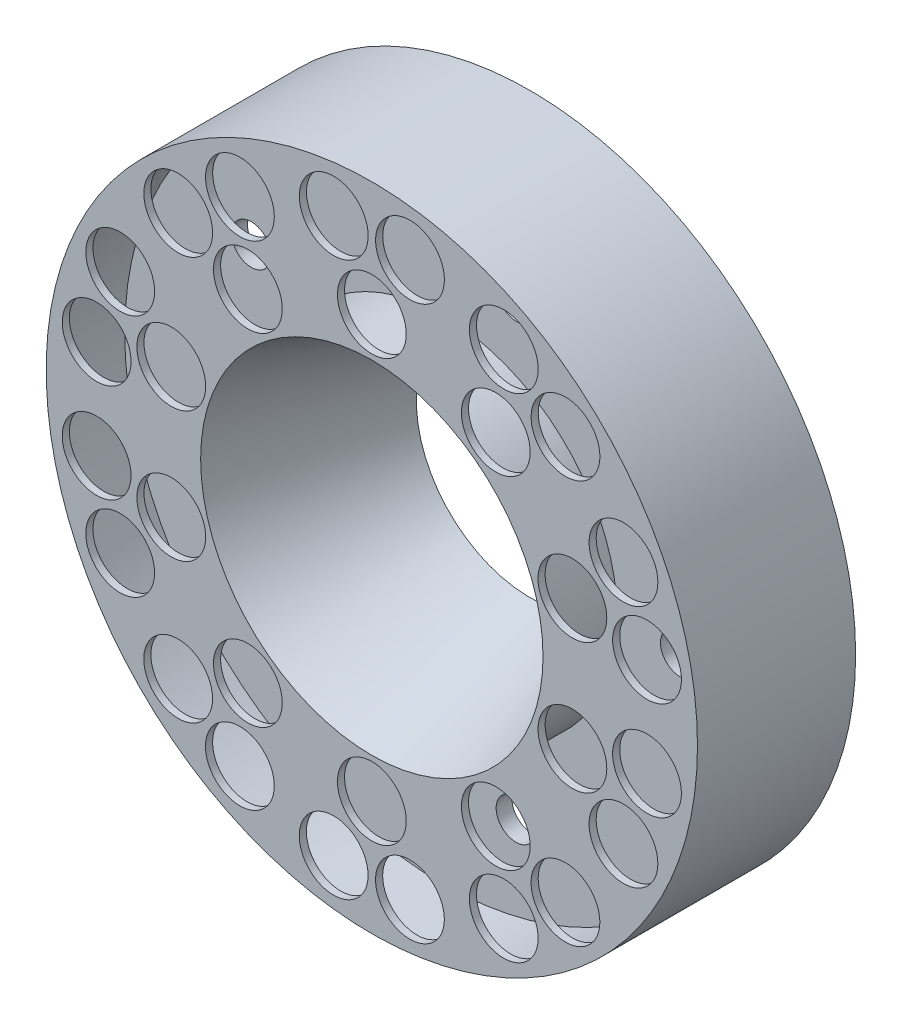
SolidWorks part; units mm, degrees
ref_plane "Front Plane" through (0, 0, 0) normal (0, 0, 1) x (1, 0, 0)
ref_plane "Top Plane" through (0, 0, 0) normal (0, 1, 0) x (1, 0, 0)
ref_plane "Right Plane" through (0, 0, 0) normal (1, 0, 0) x (0, 0, -1)
sketch "Sketch1" plane through (0, 0, 0) normal (0, 0, 1) x (1, 0, 0)
  circle A7 centre (-38.9246, 36.7467) radius 104.6074
extrude "Boss-Extrude6" add sketch "Sketch1" along normal blind 50.8
sketch "Sketch4" plane through (0, 0, 50.8) normal (0, 0, 1) x (1, 0, 0)
  circle A5 centre (-38.9246, 36.7467) radius 54.991
  dimension "D1" = 109.982
extrude "Cut-Extrude2" cut sketch "Sketch4" against normal blind 109.982 draft 20 contours A5
sketch "Sketch6" plane through (0, 0, 50.8) normal (0, 0, 1) x (1, 0, 0)
  circle A9 centre (23.2878, 101.5139) radius 11.049
  circle A10 centre (-26.663, 125.712) radius 11.049
  circle A11 centre (-38.9246, 104.4853) radius 11.049
  circle A12 centre (-51.1655, 125.712) radius 11.049
  circle A13 centre (0.8912, 91.5484) radius 11.049
  circle A14 centre (3.4648, 115.9162) radius 11.049
  circle A15 centre (49.4755, 52.577) radius 11.049
  circle A16 centre (25.4987, 57.6791) radius 11.049
  circle A17 centre (41.9038, 75.8803) radius 11.049
  circle A18 centre (41.8974, -2.4066) radius 11.049
  circle A19 centre (25.4987, 15.8143) radius 11.049
  circle A20 centre (49.4691, 20.8967) radius 11.049
  circle A21 centre (3.4481, -42.435) radius 11.049
  circle A22 centre (0.8912, -18.055) radius 11.049
  circle A23 centre (23.271, -28.0327) radius 11.049
  circle A24 centre (-51.1862, -52.2186) radius 11.049
  circle A25 centre (-38.9246, -30.992) radius 11.049
  circle A26 centre (-26.6836, -52.2186) radius 11.049
  circle A27 centre (-101.1369, -28.0206) radius 11.049
  circle A28 centre (-78.7404, -18.055) radius 11.049
  circle A29 centre (-81.314, -42.4228) radius 11.049
  circle A30 centre (-127.3247, 20.9163) radius 11.049
  circle A31 centre (-103.3479, 15.8143) radius 11.049
  circle A32 centre (-119.753, -2.387) radius 11.049
  circle A33 centre (-119.7466, 75.8999) radius 11.049
  circle A34 centre (-103.3479, 57.6791) radius 11.049
  circle A35 centre (-127.3183, 52.5966) radius 11.049
  circle A36 centre (-81.2973, 115.9283) radius 11.049
  circle A37 centre (-78.7404, 91.5484) radius 11.049
  circle A38 centre (-101.1202, 101.5261) radius 11.049
  point P63 (-38.9246, 36.7467)
  dimension "D1" = 22.098
  dimension "D2" = 10
  dimension "D3" = 22.098
  dimension "D4" = 22.098
extrude "Cut-Extrude4" cut sketch "Sketch6" against normal blind 22.86
ref_plane "Plane2" through (0, 0, 13.97) normal (0, 0, 1) x (1, 0, 0)
sketch "Sketch8" plane through (0, 0, 13.97) normal (0, 0, 1) x (1, 0, 0)
  circle A0 centre (-38.9246, 36.7467) radius 102.235
  circle A1 centre (-38.9246, 36.7467) radius 56.007
  dimension "D1" = 112.014
  dimension "D2" = 204.47
extrude "Cut-Extrude5" cut sketch "Sketch8" against normal blind 13.97 and the other way blind 8.89
ref_plane "Plane3" through (0, 0, 36.83) normal (0, 0, -1) x (-1, 0, 0)
sketch "Sketch9" plane through (0, 0, 36.83) normal (0, 0, -1) x (-1, 0, 0)
  circle A0 centre (38.9246, 36.7467) radius 102.235
  circle A1 centre (38.9246, 36.7467) radius 56.007
  dimension "D1" = 204.47
  dimension "D2" = 112.014
extrude "Cut-Extrude6" cut sketch "Sketch9" against normal blind 11.684 and the other way blind 8.89
ref_plane "Plane4" through (0, 0, 25.4) normal (0, 0, 1) x (1, 0, 0)
sketch "Sketch10" plane through (0, 0, 25.4) normal (0, 0, 1) x (1, 0, 0)
  circle A0 centre (37.2753, 36.6187) radius 6.35
  circle A1 centre (-15.4993, -35.7633) radius 6.35
  circle A2 centre (-100.6468, -7.939) radius 6.35
  circle A4 centre (-15.2558, 109.1775) radius 6.35
  circle A5 centre (-100.4964, 81.6394) radius 6.35
  point P12 (-38.9246, 36.7467)
  dimension "D2" = 5
  dimension "D1" = 12.7
extrude "Cut-Extrude7" cut sketch "Sketch10" against normal blind 2.54 and the other way blind 2.54
